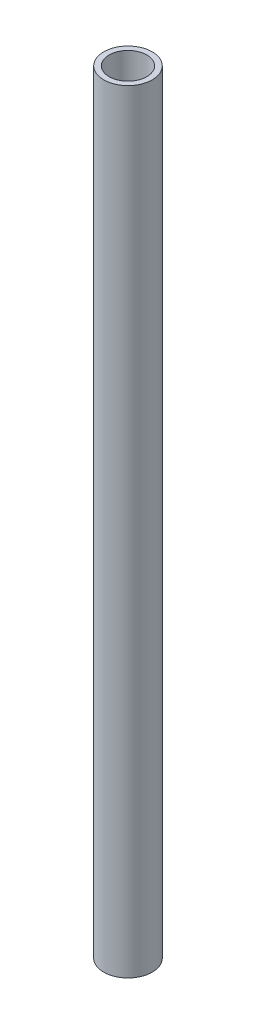
SolidWorks part; units mm, degrees
ref_plane "Front Plane" through (0, 0, 0) normal (0, 0, 1) x (1, 0, 0)
ref_plane "Top Plane" through (0, 0, 0) normal (0, 1, 0) x (1, 0, 0)
ref_plane "Right Plane" through (0, 0, 0) normal (1, 0, 0) x (0, 0, -1)
sketch "Sketch1" plane through (0, 0, 0) normal (0, 1, 0) x (1, 0, 0)
  circle A0 centre (0, 0) radius 1.22
  circle A1 centre (0, 0) radius 1.57
  dimension "D1" = 2.44
  dimension "D2" = 0.35
extrude "Boss-Extrude1" add sketch "Sketch1" along normal blind 50
